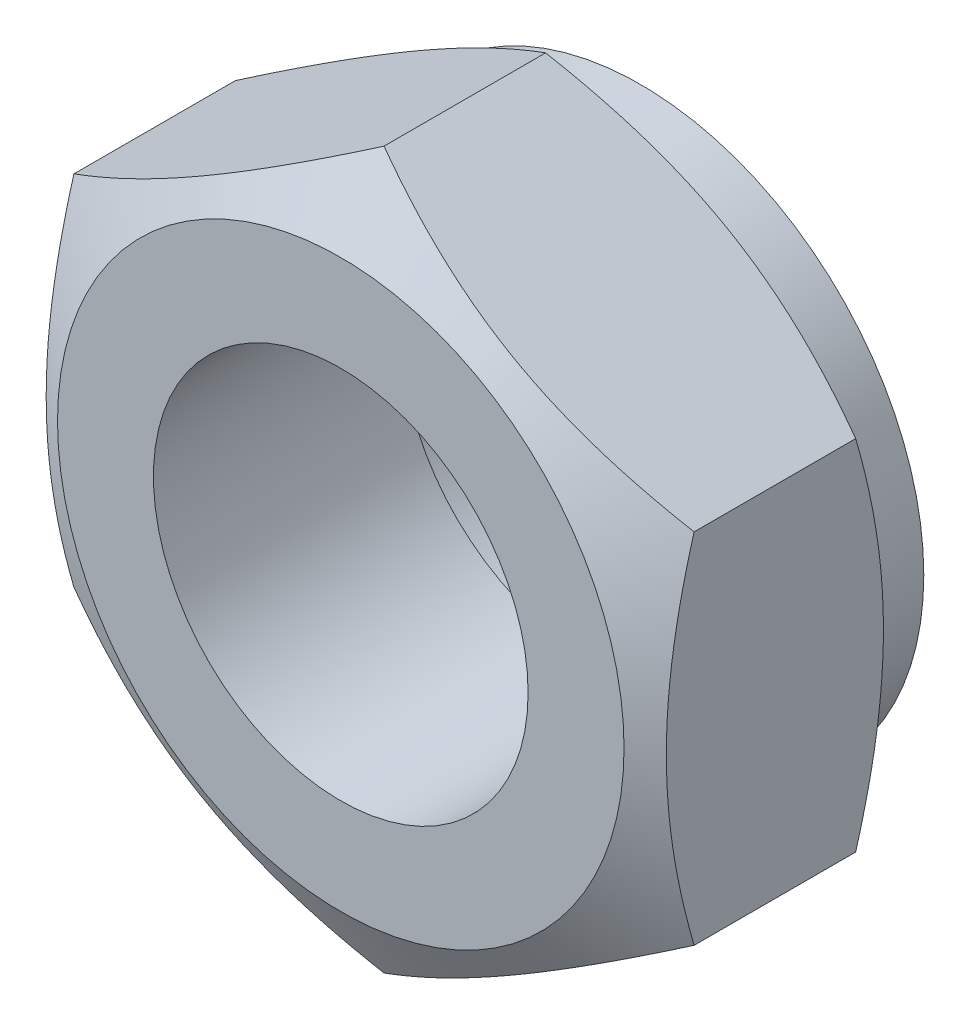
SolidWorks part; units mm, degrees
ref_plane "前视基准面" through (0, 0, 0) normal (0, 0, 1) x (1, 0, 0)
ref_plane "上视基准面" through (0, 0, 0) normal (0, 1, 0) x (1, 0, 0)
ref_plane "右视基准面" through (0, 0, 0) normal (1, 0, 0) x (0, 0, -1)
sketch "草图1" plane through (0, 0, 0) normal (0, 0, 1) x (1, 0, 0)
  line L0 (0, 13.8564) -> (0, -13.8564) construction
  line L1 (12, -6.9282) -> (12, 6.9282)
  line L2 (12, 6.9282) -> (0, 13.8564)
  line L3 (0, 13.8564) -> (-12, 6.9282)
  line L4 (-12, 6.9282) -> (-12, -6.9282)
  line L5 (-12, -6.9282) -> (0, -13.8564)
  line L6 (0, -13.8564) -> (12, -6.9282)
  circle A0 centre (0, 0) radius 12 construction
  dimension "D1" = 24
extrude "凸台-拉伸1" add sketch "草图1" along normal mid plane 9.6
sketch "草图2" plane through (0, 0, 0) normal (0, 1, 0) x (1, 0, 0)
  line L0 (0, 6.7933) -> (0, -7.0081) construction
  line L1 (5.2429, 8.1085) -> (12, 4.2)
  line L2 (5.2429, 8.1085) -> (15.4852, 8.1085)
  line L4 (12, 4.2) -> (23.5304, -2.4696)
  line L5 (12, -4.8) -> (12, 4.8) construction
  line L6 (12, -4.8) -> (12, 4.8) construction
  line L7 (23.5304, -2.4696) -> (15.4852, 8.1085)
  point P9 (11.5, 4.4892)
  point P14 (12, 4.2)
  dimension "D1" = 11.5
  dimension "D2" = 0.6
revolve "切除-旋转1" cut sketch "草图2" angle 360 about L0
mirror "镜向1" about plane through (0, 0, 0) normal (0, 0, 1) of "切除-旋转1"
sketch "草图3" plane through (0, 0, 4.8) normal (0, 0, 1) x (1, 0, 0)
  circle A0 centre (0, 0) radius 7.25
  dimension "D1" = 14.5
extrude "切除-拉伸1" cut sketch "草图3" against normal through all
cosmetic thread "装饰螺纹线1" parameters "D2"=32.25
sketch "草图4" plane through (0, 0, -4.8) normal (0, 0, -1) x (-1, 0, 0)
  circle A0 centre (0, 0) radius 8.0938
  circle A1 centre (0, 0) radius 10.9627
  circle A2 centre (0, 0) radius 10.9627
  dimension "D1" = 0
extrude "凸台-拉伸2" add sketch "草图4" along normal blind 2
